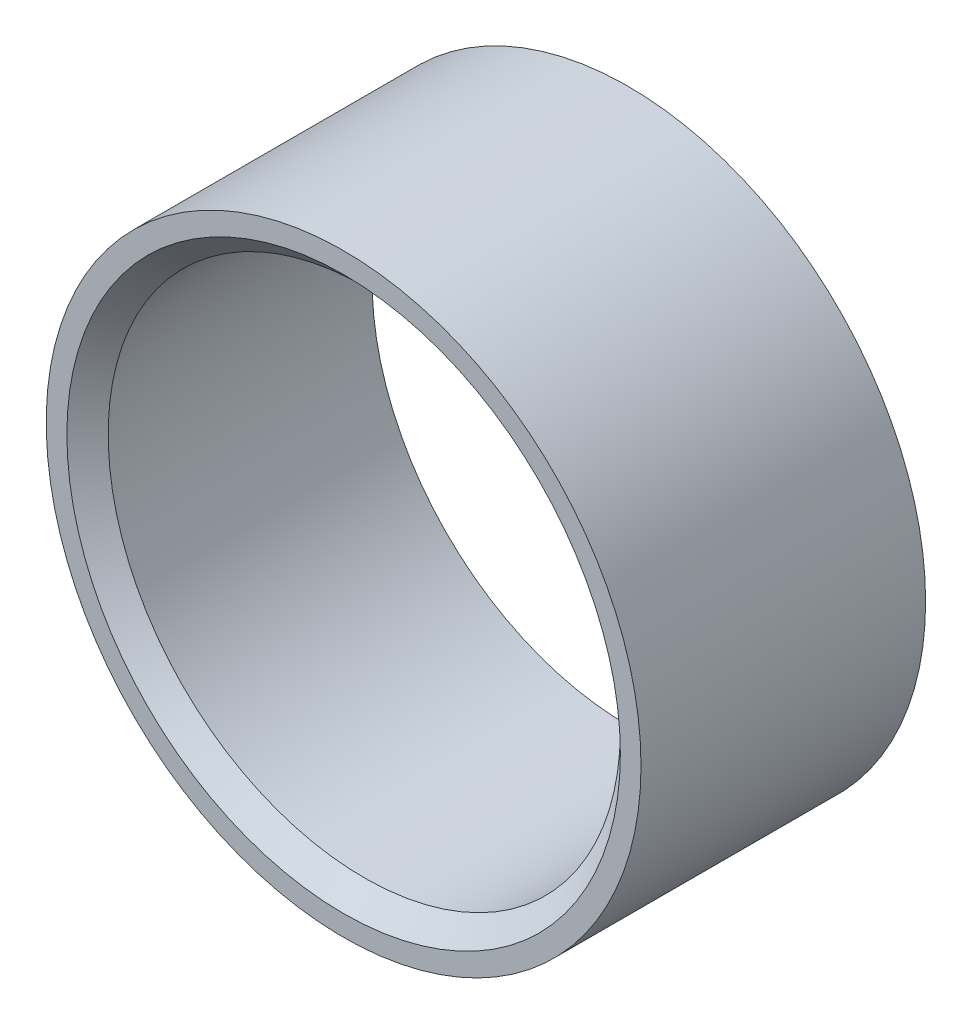
SolidWorks part; units mm, degrees
ref_plane "Front Plane" through (0, 0, 0) normal (0, 0, 1) x (1, 0, 0)
ref_plane "Top Plane" through (0, 0, 0) normal (0, 1, 0) x (1, 0, 0)
ref_plane "Right Plane" through (0, 0, 0) normal (1, 0, 0) x (0, 0, -1)
sketch "Sketch2" plane through (0, 0, 0) normal (0, 0, 1) x (1, 0, 0)
  circle A0 centre (0, 0) radius 15.748
  circle A1 centre (0, 0) radius 18.288
  dimension "D1" = 31.496
  dimension "D3" = 2.54
extrude "Boss-Extrude1" add sketch "Sketch2" along normal blind 17.5006
chamfer "Chamfer1" distance 1.27 angle 45 1 edges at (15.748, 0, 17.5006)
